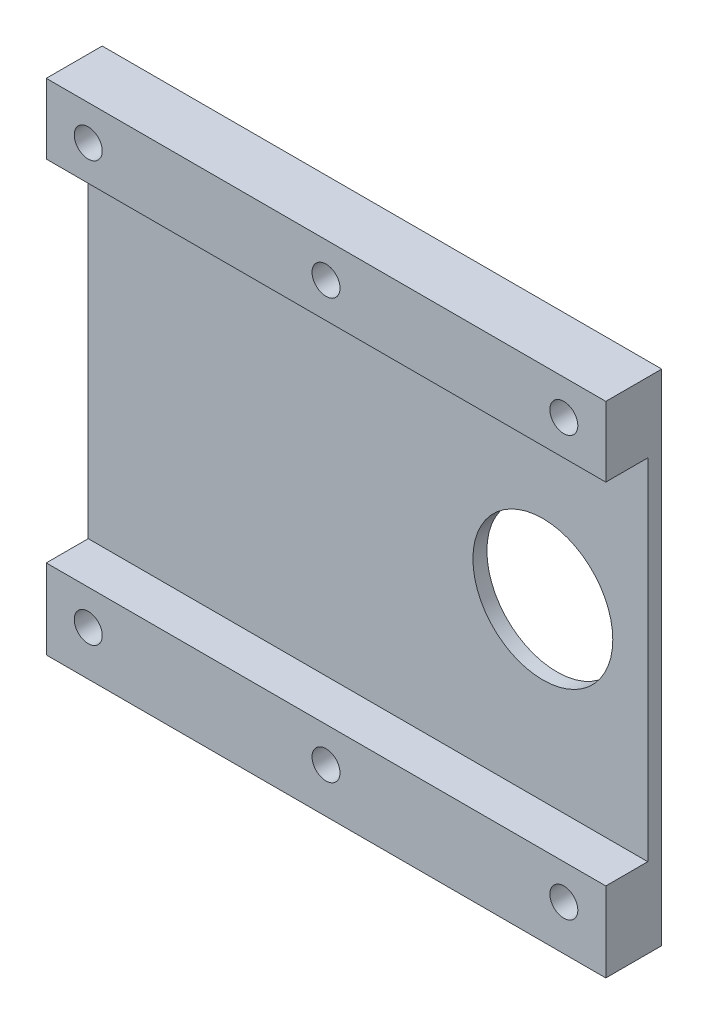
SolidWorks part; units mm, degrees
material "1060 Alloy"
ref_plane "Front Plane" through (0, 0, 0) normal (0, 0, 1) x (1, 0, 0)
ref_plane "Top Plane" through (0, 0, 0) normal (0, 1, 0) x (1, 0, 0)
ref_plane "Right Plane" through (0, 0, 0) normal (1, 0, 0) x (0, 0, -1)
sketch "Sketch1" plane through (0, 0, 0) normal (0, 0, 1) x (1, 0, 0)
  line L0 (0, 17.85) -> (0, -17.85) construction
  line L1 (-20, 17.85) -> (20, 17.85)
  line L2 (-20, 17.85) -> (-20, -17.85)
  line L3 (-20, -17.85) -> (20, -17.85)
  line L4 (20, 17.85) -> (20, -17.85)
  line L5 (-20, 17.85) -> (20, -17.85) construction
  line L6 (-20, -17.85) -> (20, 17.85) construction
  circle A0 centre (-17, 15.35) radius 1
  circle A1 centre (0, 15.35) radius 1
  circle A2 centre (17, 15.35) radius 1
  circle A3 centre (-17, -14.65) radius 1
  circle A4 centre (0, -14.65) radius 1
  circle A5 centre (17, -14.65) radius 1
  point P0 (0, 0)
  dimension "D5" = 2
  dimension "D6" = 2
  dimension "D7" = 2
  dimension "D10" = 2
  dimension "D11" = 2
  dimension "D12" = 2
  dimension "D1" = 40
  dimension "D2" = 35.7
  dimension "D3" = 17
  dimension "D4" = 17
  dimension "D8" = 30
  dimension "D9" = 2.5
extrude "Boss-Extrude1" add sketch "Sketch1" along normal blind 4
sketch "Sketch2" plane through (0, 0, 4) normal (0, 0, 1) x (1, 0, 0)
  line L0 (20, 17.85) -> (-20, 17.85) construction
  line L1 (-25, 12.85) -> (25, 12.85)
  line L2 (-25, 12.85) -> (-25, -12.15)
  line L3 (-25, -12.15) -> (25, -12.15)
  line L4 (25, 12.85) -> (25, -12.15)
  line L5 (0, 17.85) -> (0, -17.85) construction
  line L6 (-20, -17.85) -> (20, -17.85) construction
  point P0 (0, 0)
  point P6 (0, 12.85)
  dimension "D1" = 25
  dimension "D2" = 50
  dimension "D3" = 5
extrude "Cut-Extrude1" cut sketch "Sketch2" against normal blind 3
sketch "Sketch3" plane through (0, -17.85, 0) normal (0, -1, 0) x (1, 0, 0)
  line L0 (-20, 2) -> (20, 2) construction
  line L1 (-20, 4) -> (-20, 0) construction
  line L2 (20, 4) -> (20, 0) construction
  line L3 (-7.5, 2) -> (7.5, 2) construction
  line L4 (0, 4) -> (0, 0) construction
  line L5 (-20, 4) -> (20, 4) construction
  circle A0 centre (-7.5, 2) radius 1
  circle A1 centre (7.5, 2) radius 1
  point P18 (0, 2)
  dimension "D1" = 2
  dimension "D2" = 2
  dimension "D3" = 15
extrude "Cut-Extrude2" cut sketch "Sketch3" against normal blind 3
sketch "Sketch4" plane through (0, 0, 0) normal (0, 0, -1) x (-1, 0, 0)
  circle A0 centre (-12.5, 0.35) radius 5
  dimension "D1" = 10
extrude "Cut-Extrude3" cut sketch "Sketch4" against normal through all
